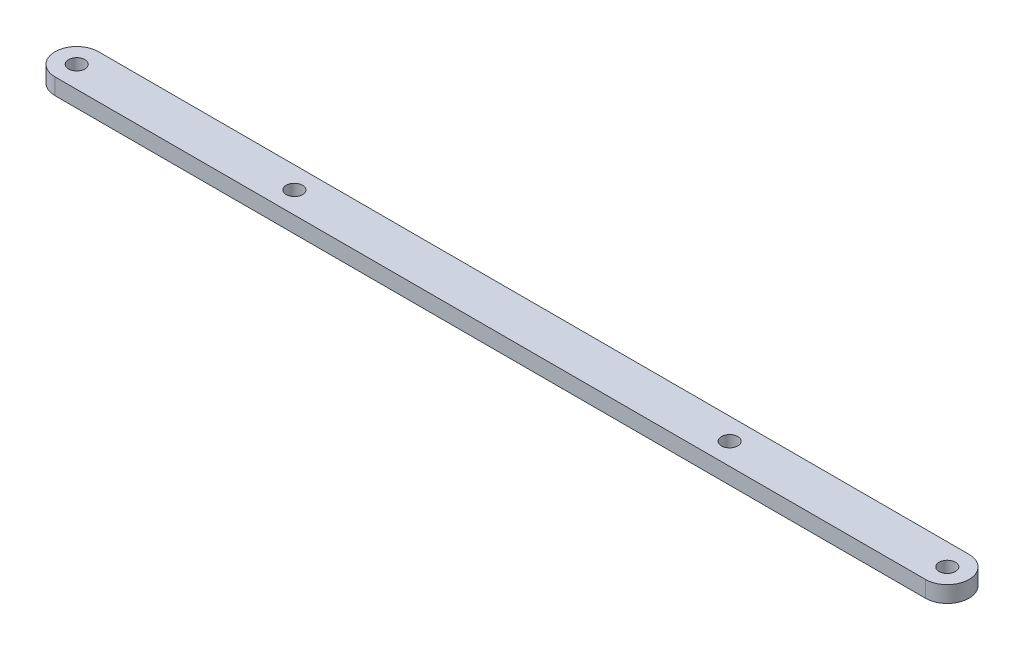
SolidWorks part; units mm, degrees
material "Pine"
ref_plane "Front Plane" through (0, 0, 0) normal (0, 0, 1) x (1, 0, 0)
ref_plane "Top Plane" through (0, 0, 0) normal (0, 1, 0) x (1, 0, 0)
ref_plane "Right Plane" through (0, 0, 0) normal (1, 0, 0) x (0, 0, -1)
sketch "Sketch1" plane through (0, 0, 0) normal (0, 1, 0) x (1, 0, 0)
  line L0 (0, 0) -> (160, 0) construction
  line L1 (0, 4) -> (160, 4)
  line L2 (0, -4) -> (160, -4)
  arc A0 (0, 4) -> (0, -4) centre (0, 0) ccw
  arc A1 (160, -4) -> (160, 4) centre (160, 0) ccw
  circle A2 centre (0, 0) radius 1.5
  circle A3 centre (160, 0) radius 1.5
  circle A4 centre (120, 0) radius 1.5
  point P3 (80, 0)
  dimension "D2" = 3
  dimension "D4" = 40
  dimension "D1" = 8
  dimension "D3" = 160
extrude "Boss-Extrude1" add sketch "Sketch1" along normal blind 3
sketch "Sketch2" plane through (0, 0, 0) normal (0, 1, 0) x (1, 0, 0)
  circle A0 centre (120, 0) radius 1.5
  circle A1 centre (120, 0) radius 1.5 construction
extrude "Boss-Extrude2" [suppressed] add sketch "Sketch2" along normal through all
sketch "Sketch3" [suppressed] plane through (0, 0, 0) normal (0, 1, 0) x (1, 0, 0)
  line L0 (0, 0) -> (100, 0) construction
  circle A0 centre (80, 0) radius 1.5
  circle A1 centre (0, 0) radius 1.5 construction
  dimension "D1" = 20
extrude "Cut-Extrude3" [suppressed] cut sketch "Sketch3" along normal through all
sketch "Sketch4" plane through (0, 0, 0) normal (0, 1, 0) x (1, 0, 0)
  line L0 (0, 0) -> (160, 0) construction
  circle A0 centre (40, 0) radius 1.5
  circle A1 centre (0, 0) radius 1.5 construction
  dimension "D1" = 40
extrude "Cut-Extrude4" cut sketch "Sketch4" along normal through all
